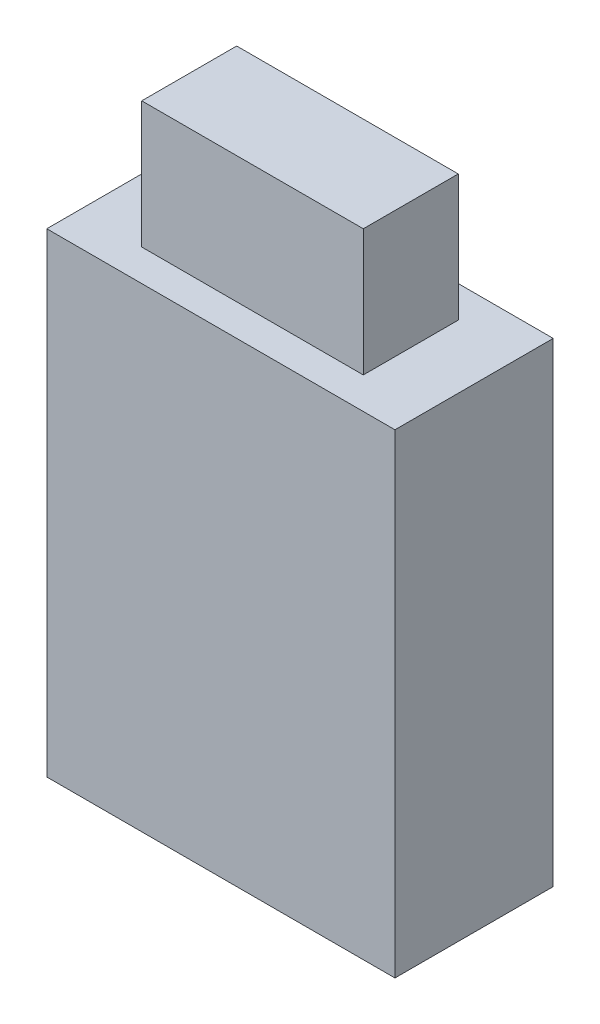
SolidWorks part; units mm, degrees
ref_plane "Front Plane" through (0, 0, 0) normal (0, 0, 1) x (1, 0, 0)
ref_plane "Top Plane" through (0, 0, 0) normal (0, 1, 0) x (1, 0, 0)
ref_plane "Right Plane" through (0, 0, 0) normal (1, 0, 0) x (0, 0, -1)
sketch "Sketch1" plane through (0, 0, 0) normal (0, 0, 1) x (1, 0, 0)
  line L1 (30, 158) -> (52, 158)
  line L2 (30, 158) -> (30, 188)
  line L3 (30, 188) -> (52, 188)
  line L4 (52, 158) -> (52, 188)
extrude "Boss-Extrude1" add sketch "Sketch1" along normal blind 10 from offset 56
sketch "Sketch2" plane through (0, 0, 0) normal (0, 0, 1) x (1, 0, 0)
  line L1 (34, 188) -> (48, 188)
  line L2 (34, 188) -> (34, 196)
  line L3 (34, 196) -> (48, 196)
  line L4 (48, 188) -> (48, 196)
extrude "Boss-Extrude2" add sketch "Sketch2" along normal blind 6 from offset 58
